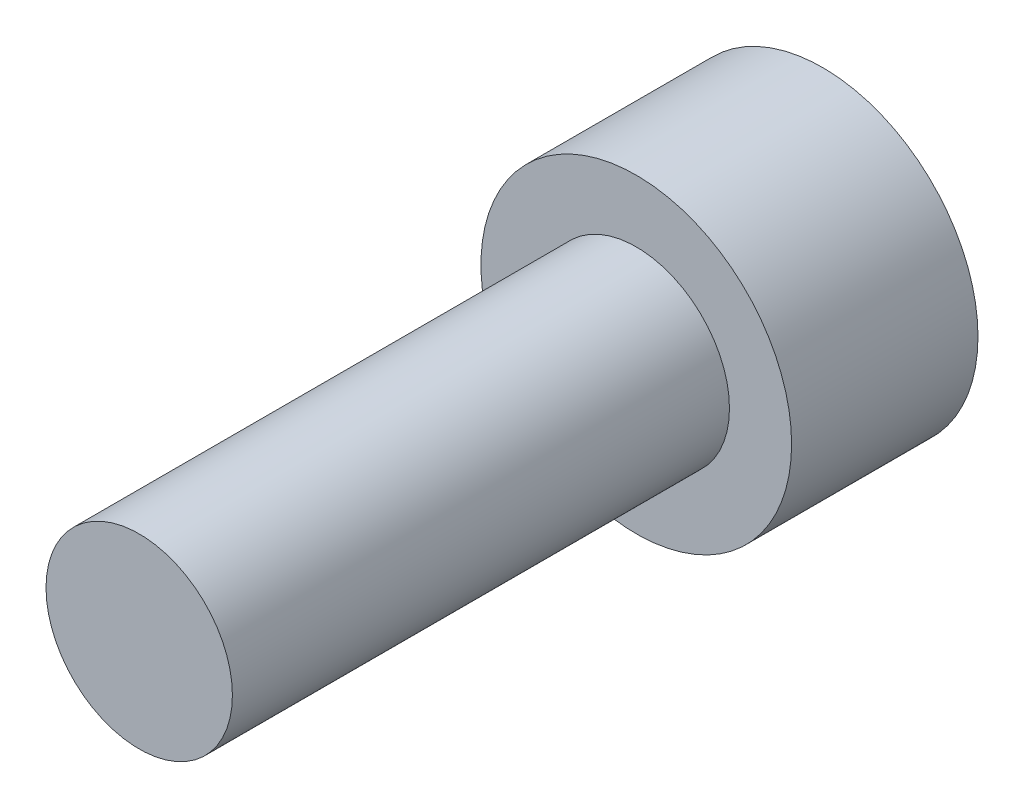
SolidWorks part; units mm, degrees
ref_plane "Front Plane" through (0, 0, 0) normal (0, 0, 1) x (1, 0, 0)
ref_plane "Top Plane" through (0, 0, 0) normal (0, 1, 0) x (1, 0, 0)
ref_plane "Right Plane" through (0, 0, 0) normal (1, 0, 0) x (0, 0, -1)
sketch "Sketch1" plane through (0, 0, 0) normal (0, 0, 1) x (1, 0, 0)
  circle A0 centre (0, 0) radius 3
  dimension "D1" = 6
extrude "Boss-Extrude1" add sketch "Sketch1" along normal blind 16
sketch "Sketch2" plane through (0, 0, 0) normal (0, 0, 1) x (1, 0, 0)
  circle A0 centre (0, 0) radius 5
  dimension "D1" = 10
extrude "Boss-Extrude2" add sketch "Sketch2" against normal blind 6
